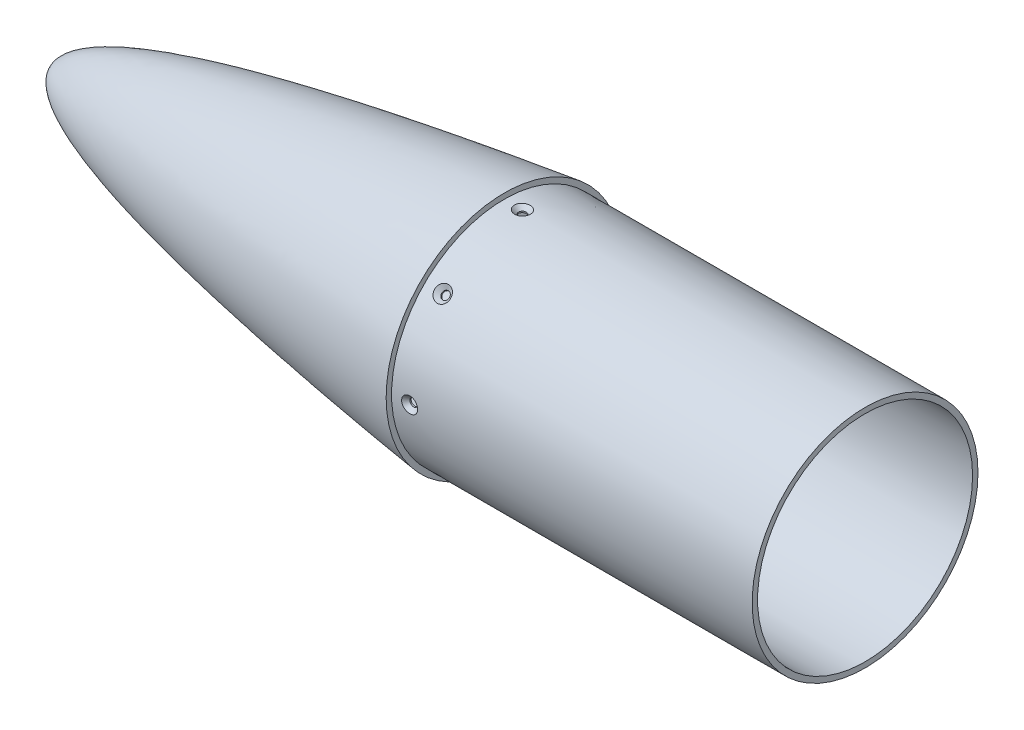
SolidWorks part; units mm, degrees
material "E-Cam Elyafı"
ref_plane "Ön Düzlem" through (0, 0, 0) normal (0, 0, 1) x (1, 0, 0)
ref_plane "Üst Düzlem" through (0, 0, 0) normal (0, 1, 0) x (1, 0, 0)
ref_plane "Sağ Düzlem" through (0, 0, 0) normal (1, 0, 0) x (0, 0, -1)
sketch "Çizim1" plane through (0, 0, 0) normal (0, 1, 0) x (1, 0, 0)
  line L0 (250, 65.5) -> (250, 62.5)
  line L1 (250, 62.5) -> (450, 62.5)
  line L2 (247, 62.0797) -> (247, 59.5)
  line L3 (247, 59.5) -> (450, 59.5)
  line L4 (3, -0.0006) -> (0, 0)
  line L5 (450, 62.5) -> (450, 59.5)
  spline S0 degree 4 poles (0, 0) (0.0001, 0.3114) (0.025, 0.827) (0.122, 1.5784) (0.3638, 2.5661) (0.6941, 3.509) (1.1732, 4.5388) (1.8403, 5.671) (2.7692, 6.948) (4.0813, 8.4307) (5.9716, 10.1968) (8.7773, 12.3667) (13.0257, 15.0718) (19.1289, 18.2539) (26.8858, 21.598) (35.8796, 24.9033) (47.9148, 28.7864) (62.5376, 32.8841) (79.7742, 37.1162) (97.1409, 40.8923) (112.076, 43.8866) (127.0428, 46.7192) (139.5367, 48.9606) (152.049, 51.1012) (164.5747, 53.1541) (174.6049, 54.7487) (183.3836, 56.105) (190.9184, 57.2429) (197.1896, 58.1739) (202.2262, 58.9119) (207.2272, 59.6361) (212.2945, 60.3603) (217.2542, 61.0619) (222.3896, 61.7784) (228.4872, 62.622) (235.1159, 63.5224) (240.8585, 64.2946) (248.3029, 65.2786) (252.745, 65.8599) (259.8843, 66.7856) (265.1918, 67.4611) (270.6078, 68.1487) (273.2826, 68.4815) (275.0459, 68.703) knots 0 0 0 0 0 0.004302 0.007145 0.010457 0.01405 0.018106 0.022838 0.028614 0.035869 0.045464 0.058585 0.07763 0.105476 0.140607 0.175394 0.210181 0.280443 0.350706 0.420968 0.4561 0.491231 0.561493 0.596625 0.631756 0.666887 0.702018 0.719584 0.73715 0.754715 0.772281 0.789847 0.807412 0.824978 0.842543 0.877675 0.89524 0.912806 0.934604 0.956403 0.978201 1 1 1 1 1 construction
  spline S1 degree 4 poles (0, 0) (0.0001, 0.3114) (0.025, 0.827) (0.122, 1.5784) (0.3638, 2.5661) (0.6941, 3.509) (1.1732, 4.5388) (1.8403, 5.671) (2.7692, 6.948) (4.0813, 8.4307) (5.9716, 10.1968) (8.7773, 12.3667) (13.0257, 15.0718) (19.1289, 18.2539) (26.8858, 21.598) (35.8796, 24.9033) (47.9148, 28.7864) (62.5376, 32.8841) (79.7742, 37.1162) (97.1409, 40.8923) (112.076, 43.8866) (127.0428, 46.7192) (139.5367, 48.9606) (152.049, 51.1012) (164.5747, 53.1541) (174.6049, 54.7487) (183.3836, 56.105) (190.9184, 57.2429) (197.1896, 58.1739) (202.2262, 58.9119) (207.2272, 59.6361) (212.2945, 60.3603) (217.2542, 61.0619) (222.3896, 61.7784) (228.4872, 62.622) (235.1159, 63.5224) (240.8585, 64.2946) (246.5402, 65.0457) (248.8512, 65.3495) (250, 65.5) knots 0 0 0 0 0 0.004302 0.007145 0.010457 0.01405 0.018106 0.022838 0.028614 0.035869 0.045464 0.058585 0.07763 0.105476 0.140607 0.175394 0.210181 0.280443 0.350706 0.420968 0.4561 0.491231 0.561493 0.596625 0.631756 0.666887 0.702018 0.719584 0.73715 0.754715 0.772281 0.789847 0.807412 0.824978 0.842543 0.877675 0.89524 0.912806 0.912806 0.912806 0.912806 0.912806
  spline S2 degree 1 poles (3, -0.0006) (247, 62.0797) knots 0 0 1 1 construction
  spline S3 degree 3 poles (3, -0.0006) (3.0001, 0.4457) (3.1041, 1.321) (3.7362, 3.136) (5.2806, 5.4132) (7.889, 7.9167) (10.9157, 10.1681) (14.1952, 12.2066) (18.7849, 14.6939) (24.7947, 17.453) (32.2364, 20.3801) (42.3512, 23.9046) (55.2309, 27.7737) (70.8833, 31.8593) (86.6592, 35.5439) (102.5184, 38.9241) (123.7434, 43.1096) (150.3867, 47.8539) (177.1144, 52.1375) (195.8669, 54.953) (206.5759, 56.5131) (213.2889, 57.472) (218.6359, 58.2253) (222.7077, 58.7932) (226.6559, 59.3398) (230.7277, 59.8977) (234.8034, 60.4513) (238.0732, 60.8921) (240.7211, 61.2467) (242.7772, 61.5207) (244.922, 61.8052) (246.3033, 61.9878) (247, 62.0797) knots 0 0 0 0 0.007034 0.014068 0.028137 0.042205 0.056274 0.070342 0.084411 0.112547 0.140684 0.168821 0.225095 0.281369 0.337642 0.393916 0.45019 0.562737 0.675285 0.731558 0.759695 0.787832 0.801901 0.815969 0.830037 0.844106 0.858174 0.872243 0.879277 0.886311 0.893345 0.90038 0.90038 0.90038 0.90038
  dimension "D1" = 3
  dimension "D2" = 200
  dimension "D3" = 250
  dimension "D4" = 3
  dimension "D5" = 3
  dimension "D6" = 3
  dimension "D7" = 3
  dimension "D8" = 3
revolve "Döndür1" add sketch "Çizim1" angle 360 about L4
ref_plane "Düzlem3" through (450, 0, 0) normal (1, 0, 0) x (0, 0, -1)
ref_plane "Düzlem4" through (250, 0, 0) normal (1, 0, 0) x (0, 0, -1)
sketch "Çizim30" plane through (450, 0, 0) normal (1, 0, 0) x (0, 0, -1)
  line L0 (-0.0006, 0) -> (-0.0927, 62.5927) construction
  line L1 (11.4162, 62.5927) -> (-11.6015, 62.5927) construction
  ellipse E0 centre (-0.0927, 0) end of major axis (-0.0927, 62.5927) minor radius 62.5927 construction
  point P12 (-0.0927, 62.5927)
sketch "Çizim31" plane through (250, 0, 0) normal (1, 0, 0) x (0, 0, -1)
  line L0 (0, 0) -> (-0.0927, 62.5927) construction
ref_plane "Düzlem5" through (0, 62.5927, 0) normal (0, 1, 0) x (1, 0, 0)
sketch "Çizim32" plane through (0, 62.5927, 0) normal (0, 1, 0) x (1, 0, 0)
  line L0 (250, -0.0463) -> (260, -0.0463) construction
  line L1 (250, 0) -> (250, -0.0927) construction
  point P1 (260, -0.0463)
  point P8 (260, -0.0463)
hole_wizard "M4 Altıgen Alyan Havşa Başlı Kör Vida İçin Havşa1" positions "Çizim32" profile "Çizim33" countersink size "M4" standard "ISO"
sketch "Çizim33" plane through (260, 62.5927, 0.0463) normal (1, 0, 0) x (0, 0, 1)
  line L0 (0, 0) -> (0, 13.5919)
  line L1 (0, 13.5919) -> (2.15, 12.3)
  line L2 (2.15, 12.3) -> (2.15, 2.33)
  line L3 (2.15, 2.33) -> (4.48, 0)
  line L5 (4.48, 0) -> (0, 0)
  line L6 (-2.15, 2.33) -> (-4.48, 0) construction
  line L10 (0, 13.5919) -> (-2.15, 12.3) construction
  line L11 (0, -6.35) -> (0, 107.95) construction
  dimension "Hole Dia." = 4.3
  dimension "Hole Depth" = 12.3
  dimension "Near C'Sink Dia." = 8.96
  dimension "Near C'Sink Angle" = 90
  dimension "Drill Angle" = 118
pattern_circular "Dairesel Kaplama3" count 8 every 45 about axis through (449.9871, 0, 0.0927) along (1, 0, 0.0002) of "M4 Altıgen Alyan Havşa Başlı Kör Vida İçin Havşa1"
